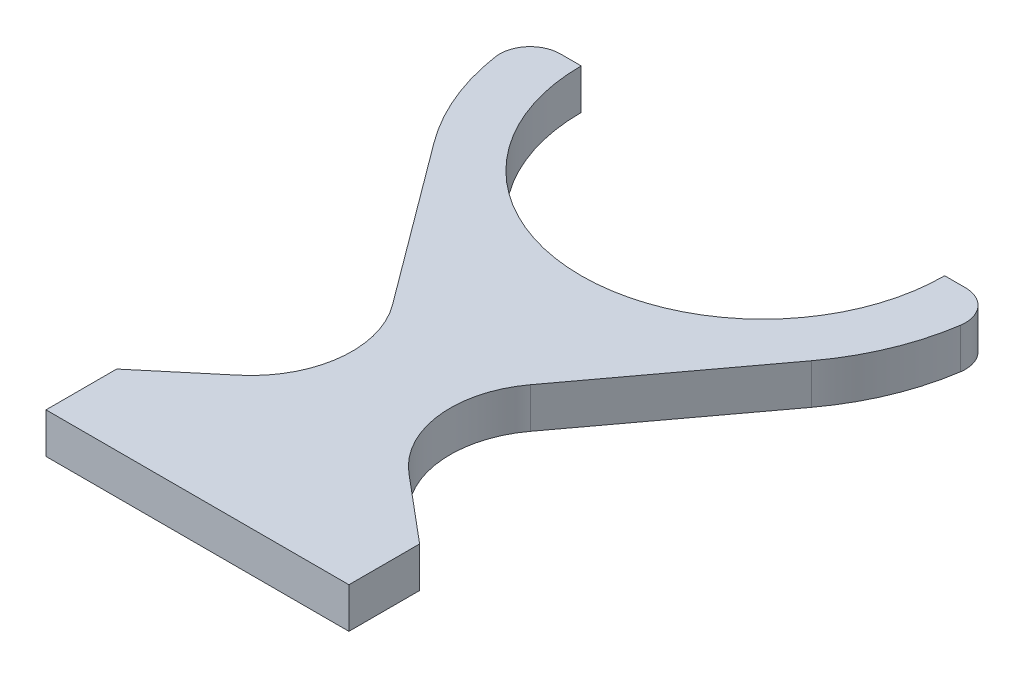
SolidWorks part; units mm, degrees
material "PTFE (general)"
ref_plane "Front Plane" through (0, 0, 0) normal (0, 0, 1) x (1, 0, 0)
ref_plane "Top Plane" through (0, 0, 0) normal (0, 1, 0) x (1, 0, 0)
ref_plane "Right Plane" through (0, 0, 0) normal (1, 0, 0) x (0, 0, -1)
sketch "Sketch1" plane through (0, 0, 0) normal (0, 1, 0) x (1, 0, 0)
  line L0 (-75, 35) -> (-75, 0)
  line L1 (-75, 0) -> (0, 0)
  line L2 (0, 0) -> (0, 280)
  line L3 (-75, 35) -> (-6.056, 92.8509)
  line L4 (-6.056, 92.8509) -> (-145, 280)
  line L5 (0, 280) -> (-145, 280)
  dimension "D1" = 35
  dimension "D2" = 75
  dimension "D3" = 280
  dimension "D4" = 230
  dimension "D5" = 90
  dimension "D6" = 145
extrude "Boss-Extrude1" add sketch "Sketch1" along normal blind 20
fillet "Fillet1" radius 50 1 edges at (-6.056, 10, -92.8509)
sketch "Sketch5" plane through (0, 20, 0) normal (0, 1, 0) x (1, 0, 0)
  line L0 (0, 190) -> (0, 280)
  line L1 (0, 280) -> (-90, 280)
  line L2 (-145, 280) -> (-93.4764, 210.6009)
  line L3 (-116.422, 280) -> (-145, 280)
  arc A0 (-90, 280) -> (0, 190) centre (0, 280) ccw
  arc A1 (-116.422, 280) -> (-93.4764, 210.6009) centre (0, 280) ccw
  dimension "D1" = 180
extrude "Cut-Extrude3" cut sketch "Sketch5" against normal up to surface (20 mm away) up to face at (-51.1096, 0, -112.3795)
fillet "Fillet3" radius 15 1 edges at (-116.422, 10, -280)
mirror "Mirror2" about plane through (0, 20, 0) normal (-1, 0, 0) of "Boss-Extrude1", "Fillet1", "Cut-Extrude3", "Fillet3"
